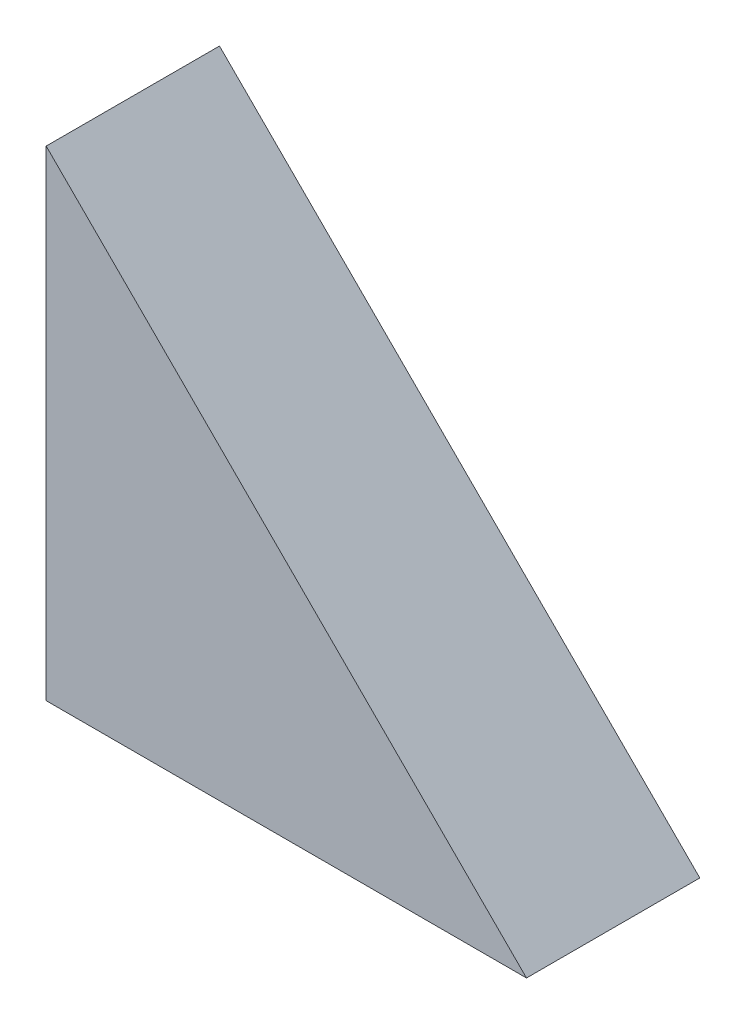
SolidWorks part; units mm, degrees
ref_plane "Front Plane" through (0, 0, 0) normal (0, 0, 1) x (1, 0, 0)
ref_plane "Top Plane" through (0, 0, 0) normal (0, 1, 0) x (1, 0, 0)
ref_plane "Right Plane" through (0, 0, 0) normal (1, 0, 0) x (0, 0, -1)
sketch "Sketch3" plane through (0, 0, 0) normal (0, 0, 1) x (1, 0, 0)
  line L0 (0, 0) -> (97, 0)
  line L1 (97, 0) -> (0, 97)
  line L2 (0, 97) -> (0, 0)
  dimension "D1" = 97
extrude "Boss-Extrude1" add sketch "Sketch3" along normal blind 35
